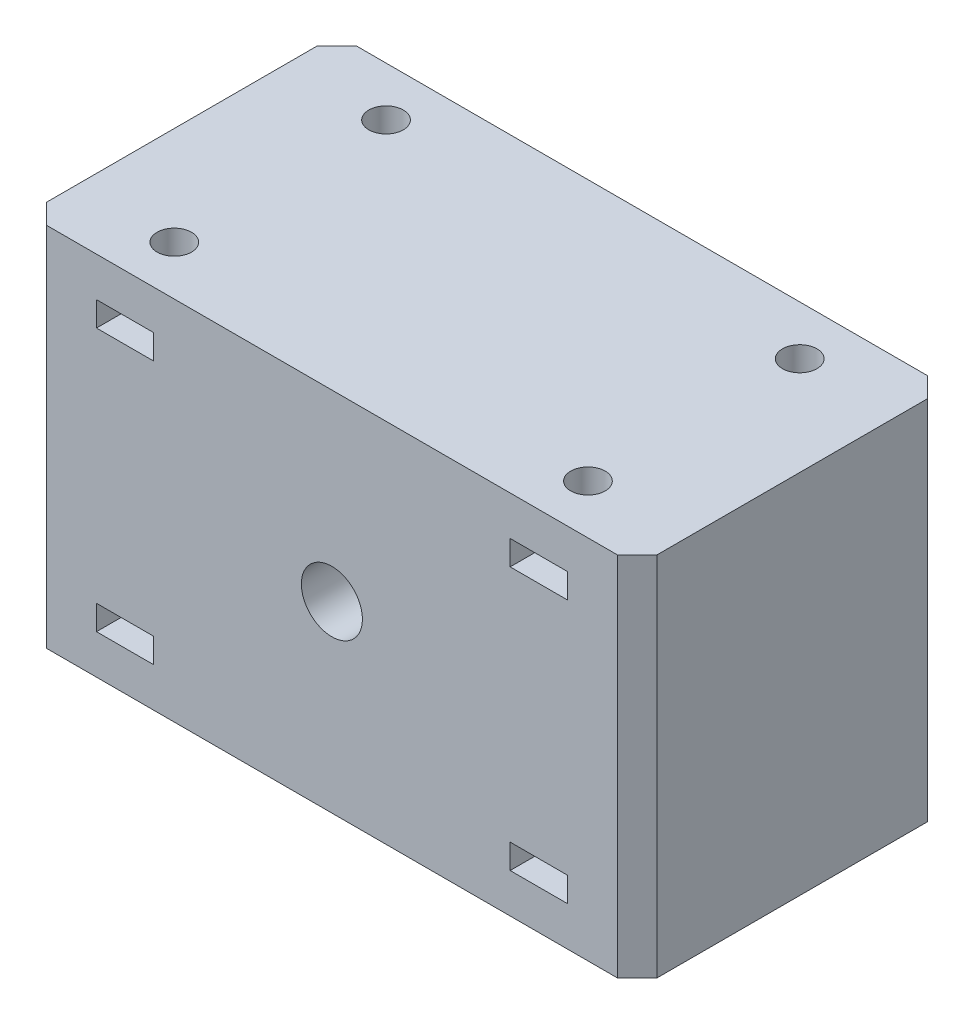
SolidWorks part; units mm, degrees
ref_plane "Front Plane" through (0, 0, 0) normal (0, 0, 1) x (1, 0, 0)
ref_plane "Top Plane" through (0, 0, 0) normal (0, 1, 0) x (1, 0, 0)
ref_plane "Right Plane" through (0, 0, 0) normal (1, 0, 0) x (0, 0, -1)
ref_plane "Plane1" through (0, -18.6, 0) normal (0, 1, 0) x (1, 0, 0)
ref_plane "Plane2" through (0, 18.6, 0) normal (0, 1, 0) x (1, 0, 0)
sketch "Sketch1" plane through (0, 18.6, 0) normal (0, 1, 0) x (1, 0, 0)
  line L0 (32, -7) -> (32, 7) construction
  line L1 (32, -7) -> (32, 7)
  line L2 (-32, 7) -> (-32, -7) construction
  line L3 (-32, 7) -> (-32, -7)
ref_plane "Plane3" through (0, 0, 15.75) normal (0, 0, 1) x (1, 0, 0)
ref_plane "Plane4" through (0, 0, -15.75) normal (0, 0, 1) x (1, 0, 0)
sketch "Sketch2" plane through (0, 0, 0) normal (0, 1, 0) x (1, 0, 0)
  line L0 (-32, 7) -> (-32, -7) construction
  line L1 (32, -7) -> (32, 7) construction
  line L2 (-32, 7) -> (-32, -7) construction
  line L3 (32, -7) -> (32, 7) construction
  line L4 (-55, 15.75) -> (55, 15.75) construction
  line L5 (-31, 15.75) -> (31, 15.75)
  line L6 (-31, 15.75) -> (-31, -15.75)
  line L7 (-31, -15.75) -> (31, -15.75)
  line L8 (31, 15.75) -> (31, -15.75)
  line L9 (-55, -15.75) -> (55, -15.75) construction
  point P12 (0, 15.75)
  dimension "D1" = 1
extrude "Boss-Extrude1" add sketch "Sketch2" along normal up to surface (18.6 mm away) and the other way up to surface (18.6 mm away) up to plane "Plane2" other way up to plane "Plane1"
sketch "Sketch3" plane through (0, 0, 0) normal (0, 0, 1) x (1, 0, 0)
  circle A0 centre (0, 0) radius 3.1
  dimension "D1" = 6.2
extrude "Cut-Extrude1" cut sketch "Sketch3" against normal through all and the other way through all
sketch "Sketch4" plane through (0, 0, 0) normal (0, 1, 0) x (1, 0, 0)
  line L1 (-21, -10.75) -> (21, -10.75) construction
  line L2 (-21, -10.75) -> (-21, 10.75) construction
  line L3 (-21, 10.75) -> (21, 10.75) construction
  line L4 (31, 15.75) -> (-31, 15.75)
  line L5 (31, -15.75) -> (31, 15.75)
  line L6 (-31, -15.75) -> (31, -15.75)
  line L7 (-31, 15.75) -> (-31, -15.75)
  line L8 (31, 15.75) -> (-31, 15.75) construction
  line L9 (31, -15.75) -> (31, 15.75) construction
  line L10 (-31, -15.75) -> (31, -15.75) construction
  line L11 (-31, 15.75) -> (-31, -15.75) construction
  line L12 (21, -10.75) -> (21, 10.75) construction
  line L13 (-21, -10.75) -> (21, 10.75) construction
  line L14 (-21, 10.75) -> (21, -10.75) construction
  circle A0 centre (-21, 10.75) radius 1.75
  circle A1 centre (21, 10.75) radius 1.75
  circle A2 centre (21, -10.75) radius 1.75
  circle A3 centre (-21, -10.75) radius 1.75
  point P2 (0, 0)
  dimension "D2" = 3.5
  dimension "D3" = 10
  dimension "D4" = 5
  dimension "D1" = 0
sketch "Sketch5" plane through (0, 18.6, 0) normal (0, 1, 0) x (1, 0, 0)
  circle A1 centre (-21, -10.75) radius 1.75
  circle A2 centre (-21, -10.75) radius 1.75
  circle A3 centre (21, -10.75) radius 1.75
  circle A4 centre (21, -10.75) radius 1.75
  circle A5 centre (21, 10.75) radius 1.75
  circle A6 centre (21, 10.75) radius 1.75
  circle A7 centre (-21, 10.75) radius 1.75
  circle A8 centre (-21, 10.75) radius 1.75
  dimension "D1" = 0
  dimension "D2" = 0
  dimension "D3" = 0
  dimension "D4" = 0
extrude "Cut-Extrude2" cut sketch "Sketch5" against normal blind 10
sketch "Sketch6" plane through (0, -18.6, 0) normal (0, -1, 0) x (1, 0, 0)
  circle A1 centre (-21, 10.75) radius 1.75
  circle A2 centre (-21, 10.75) radius 1.75
  circle A3 centre (21, 10.75) radius 1.75
  circle A4 centre (21, 10.75) radius 1.75
  circle A5 centre (21, -10.75) radius 1.75
  circle A6 centre (21, -10.75) radius 1.75
  circle A7 centre (-21, -10.75) radius 1.75
  circle A8 centre (-21, -10.75) radius 1.75
  dimension "D1" = 0
  dimension "D2" = 0
  dimension "D3" = 0
  dimension "D4" = 0
extrude "Cut-Extrude3" cut sketch "Sketch6" against normal blind 10
sketch "Sketch7" plane through (0, 18.6, 0) normal (0, 1, 0) x (1, 0, 0)
  line L0 (-21, 15.75) -> (-21, -15.75) construction
  line L1 (31, 15.75) -> (-31, 15.75) construction
  line L2 (-31, -15.75) -> (31, -15.75) construction
  line L3 (21, 15.75) -> (21, -15.75) construction
  line L4 (-21, -10.75) -> (-21, 10.75) construction
  line L5 (21, -10.75) -> (21, 10.75) construction
  line L6 (31, 15.75) -> (-31, 15.75) construction
  line L7 (-23.9, 15.75) -> (-18.1, 15.75)
  line L8 (-23.9, 15.75) -> (-23.9, 6.75)
  line L9 (-23.9, 6.75) -> (-18.1, 6.75)
  line L10 (-18.1, 15.75) -> (-18.1, 6.75)
  line L11 (-21, 0) -> (21, 0) construction
  line L12 (0, 10.75) -> (0, -10.75) construction
  line L13 (-21, 10.75) -> (21, 10.75) construction
  line L14 (-21, -10.75) -> (21, -10.75) construction
  line L15 (0, -17.325) -> (0, 17.325) construction
  line L16 (23.9, 6.75) -> (18.1, 6.75)
  line L17 (18.1, 15.75) -> (18.1, 6.75)
  line L18 (23.9, 15.75) -> (18.1, 15.75)
  line L19 (23.9, 15.75) -> (23.9, 6.75)
  line L20 (-20.46, 0) -> (20.46, 0) construction
  line L21 (23.9, -15.75) -> (23.9, -6.75)
  line L22 (23.9, -15.75) -> (18.1, -15.75)
  line L23 (18.1, -15.75) -> (18.1, -6.75)
  line L24 (23.9, -6.75) -> (18.1, -6.75)
  line L25 (-23.9, -6.75) -> (-18.1, -6.75)
  line L26 (-18.1, -15.75) -> (-18.1, -6.75)
  line L27 (-23.9, -15.75) -> (-18.1, -15.75)
  line L28 (-23.9, -15.75) -> (-23.9, -6.75)
  point P19 (-21, 6.75)
  point P20 (-21, 10.75)
  dimension "D1" = 5.8
  dimension "D2" = 4
extrude "Cut-Extrude4" cut sketch "Sketch7" against normal blind 2.5 from offset 4 offset against normal yes
sketch "Sketch8" plane through (0, -18.6, 0) normal (0, -1, 0) x (1, 0, 0)
  line L4 (-23.9, -15.75) -> (-18.1, -15.75)
  line L5 (-18.1, -15.75) -> (-18.1, -6.75)
  line L6 (-18.1, -6.75) -> (-23.9, -6.75)
  line L7 (-23.9, -6.75) -> (-23.9, -15.75)
  line L8 (-23.9, -15.75) -> (-18.1, -15.75)
  line L9 (-18.1, -15.75) -> (-18.1, -6.75)
  line L10 (-18.1, -6.75) -> (-23.9, -6.75)
  line L11 (-23.9, -6.75) -> (-23.9, -15.75)
  line L12 (-23.9, 6.75) -> (-18.1, 6.75)
  line L13 (-18.1, 6.75) -> (-18.1, 15.75)
  line L14 (-18.1, 15.75) -> (-23.9, 15.75)
  line L15 (-23.9, 15.75) -> (-23.9, 6.75)
  line L16 (-23.9, 6.75) -> (-18.1, 6.75)
  line L17 (-18.1, 6.75) -> (-18.1, 15.75)
  line L18 (-18.1, 15.75) -> (-23.9, 15.75)
  line L19 (-23.9, 15.75) -> (-23.9, 6.75)
  line L20 (23.9, 6.75) -> (23.9, 15.75)
  line L21 (18.1, 6.75) -> (23.9, 6.75)
  line L22 (18.1, 15.75) -> (18.1, 6.75)
  line L23 (23.9, 15.75) -> (18.1, 15.75)
  line L24 (23.9, 6.75) -> (23.9, 15.75)
  line L25 (18.1, 6.75) -> (23.9, 6.75)
  line L26 (18.1, 15.75) -> (18.1, 6.75)
  line L27 (23.9, 15.75) -> (18.1, 15.75)
  line L28 (23.9, -6.75) -> (18.1, -6.75)
  line L29 (18.1, -6.75) -> (18.1, -15.75)
  line L30 (18.1, -15.75) -> (23.9, -15.75)
  line L31 (23.9, -15.75) -> (23.9, -6.75)
  line L32 (23.9, -6.75) -> (18.1, -6.75)
  line L33 (18.1, -6.75) -> (18.1, -15.75)
  line L34 (18.1, -15.75) -> (23.9, -15.75)
  line L35 (23.9, -15.75) -> (23.9, -6.75)
  dimension "D1" = 0
  dimension "D2" = 0
  dimension "D3" = 0
  dimension "D4" = 0
extrude "Cut-Extrude5" cut sketch "Sketch8" against normal blind 2.5 from offset 4 offset against normal yes
chamfer "Chamfer1" distance 2 angle 45 4 edges at (-31, 0, -15.75) (31, 0, -15.75) (-31, 0, 15.75) (31, 0, 15.75)
